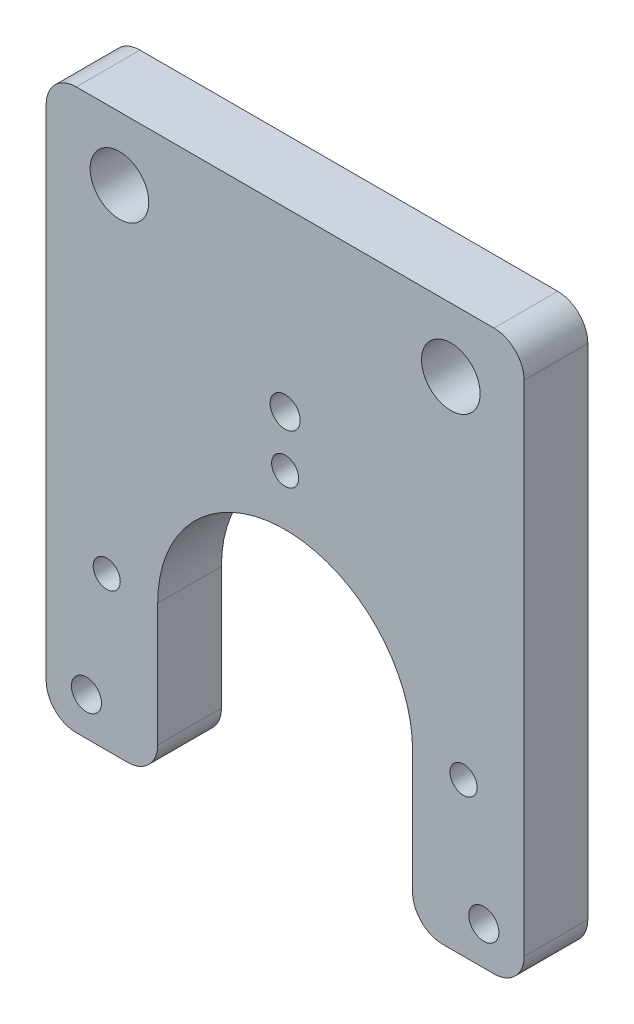
SolidWorks part; units mm, degrees
material "Beech"
ref_plane "Front Plane" through (0, 0, 0) normal (0, 0, 1) x (1, 0, 0)
ref_plane "Top Plane" through (0, 0, 0) normal (0, 1, 0) x (1, 0, 0)
ref_plane "Right Plane" through (0, 0, 0) normal (1, 0, 0) x (0, 0, -1)
sketch "Sketch1" plane through (0, 0, 0) normal (0, 0, 1) x (1, 0, 0)
  line L0 (23.8125, -25.258) -> (23.8125, 55.738) construction
  line L1 (0, 0) -> (11.1125, 0)
  line L2 (0, 0) -> (0, 55.738)
  line L3 (0, 55.738) -> (47.625, 55.738)
  line L4 (47.625, 0) -> (47.625, 55.738)
  line L5 (0, 15.24) -> (47.625, 15.24) construction
  line L6 (7.3025, 55.738) -> (7.3025, 49.388) construction
  line L7 (0, 55.738) -> (47.625, 0) construction
  line L8 (23.8125, 27.94) -> (23.8125, 38.1) construction
  line L9 (11.1125, 15.24) -> (11.1125, 0)
  line L10 (36.5125, 15.24) -> (36.5125, 0)
  line L11 (36.5125, 0) -> (47.625, 0)
  circle A0 centre (7.3025, 49.388) radius 2.921
  circle A1 centre (40.3225, 49.388) radius 2.921
  circle A2 centre (6.0325, 15.24) radius 1.35
  circle A3 centre (23.8125, 33.02) radius 1.35
  circle A4 centre (41.5925, 15.24) radius 1.35
  arc A8 (36.5125, 15.24) -> (11.1125, 15.24) centre (23.8125, 15.24) ccw
  circle A9 centre (23.8125, 38.1) radius 1.5
  circle A10 centre (43.6098, 3.81) radius 1.5
  circle A11 centre (4.0152, 3.81) radius 1.5
  point P9 (7.3025, 55.738)
  point P23 (23.8125, 15.24)
  point P39 (23.8125, 15.24)
  dimension "D5" = 5.842
  dimension "D6" = 25.4
  dimension "D8" = 3
  dimension "D12" = 2.7
  dimension "D13" = 17.78
  dimension "D1" = 47.625
  dimension "D2" = 40.498
  dimension "D3" = 16.51
  dimension "D4" = 6.35
  dimension "D7" = 10.16
  dimension "D10" = 15.24
  dimension "D9" = 3
  dimension "D11" = 3
extrude "Boss-Extrude1" add sketch "Sketch1" along normal blind 6.35
fillet "Fillet1" radius 3 6 edges at (0, 55.738, 3.175) (47.625, 55.738, 3.175) (47.625, 0, 3.175) (36.5125, 0, 3.175) (11.1125, 0, 3.175) (0, 0, 3.175)
